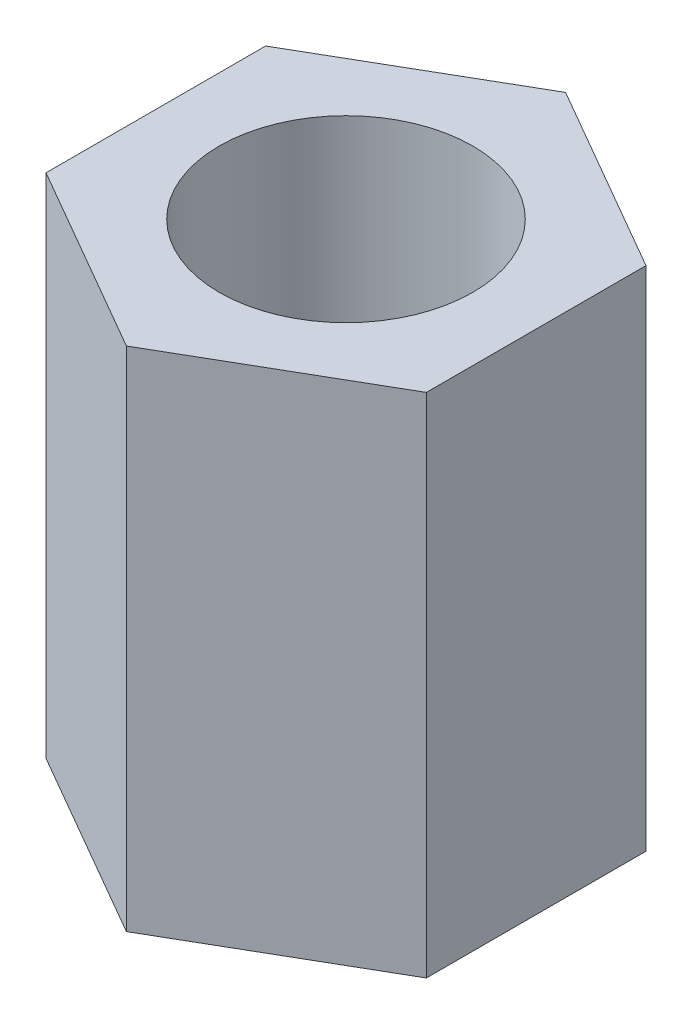
SolidWorks part; units mm, degrees
ref_plane "Front Plane" through (0, 0, 0) normal (0, 0, 1) x (1, 0, 0)
ref_plane "Top Plane" through (0, 0, 0) normal (0, 1, 0) x (1, 0, 0)
ref_plane "Right Plane" through (0, 0, 0) normal (1, 0, 0) x (0, 0, -1)
sketch "Sketch1" plane through (0, 0, 0) normal (0, 1, 0) x (1, 0, 0)
  line L1 (0, 2.5981) -> (-2.25, 1.299)
  line L2 (-2.25, 1.299) -> (-2.25, -1.299)
  line L3 (-2.25, -1.299) -> (0, -2.5981)
  line L4 (0, -2.5981) -> (2.25, -1.299)
  line L5 (2.25, -1.299) -> (2.25, 1.299)
  line L6 (2.25, 1.299) -> (0, 2.5981)
  circle A0 centre (0, 0) radius 2.25 construction
  dimension "D1" = 4.5
extrude "Boss-Extrude1" add sketch "Sketch1" along normal blind 6
sketch "Sketch2" plane through (0, 6, 0) normal (0, 1, 0) x (1, 0, 0)
  circle A0 centre (0, 0) radius 1.5
  dimension "D1" = 3
extrude "Cut-Extrude1" cut sketch "Sketch2" against normal blind 25
